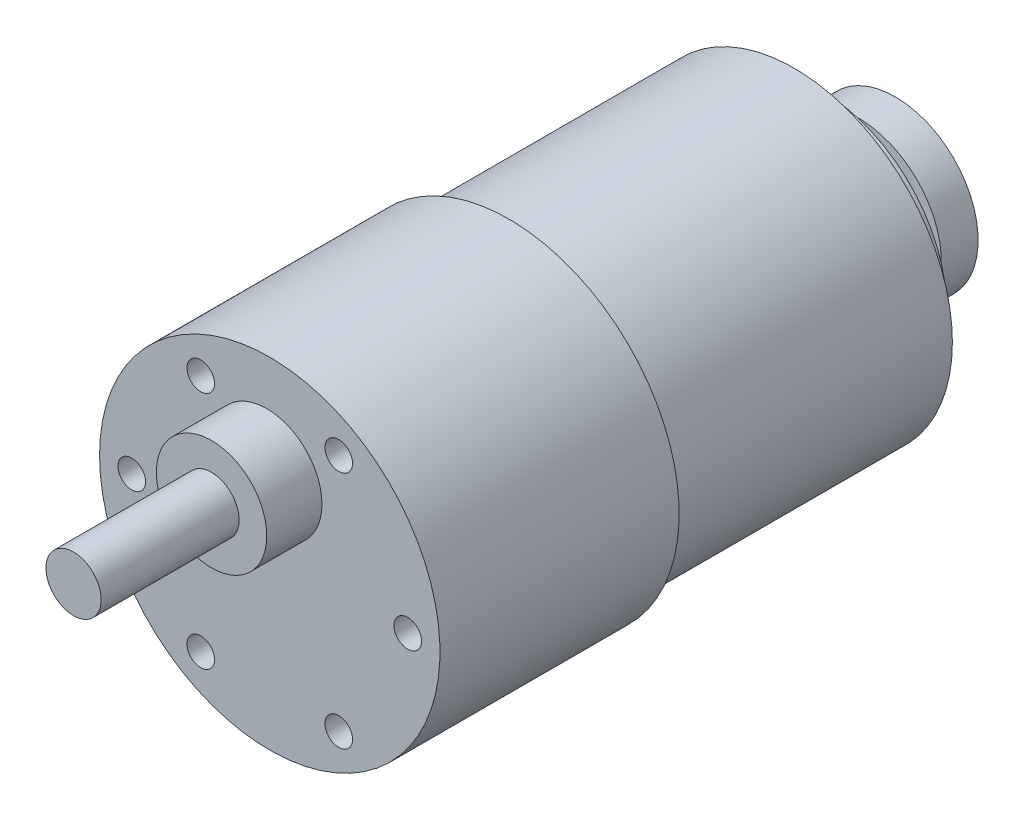
SolidWorks part; units mm, degrees
ref_plane "Plan de face" through (0, 0, 0) normal (0, 0, 1) x (1, 0, 0)
ref_plane "Plan de dessus" through (0, 0, 0) normal (0, 1, 0) x (1, 0, 0)
ref_plane "Plan de droite" through (0, 0, 0) normal (1, 0, 0) x (0, 0, -1)
sketch "Esquisse1" plane through (0, 0, 0) normal (0, 0, 1) x (1, 0, 0)
  circle A0 centre (0, 0) radius 18.5
  dimension "D1" = 37
extrude "Boss.-Extru.1" add sketch "Esquisse1" along normal blind 26
sketch "Esquisse2" plane through (0, 0, 0) normal (0, 0, -1) x (-1, 0, 0)
  circle A0 centre (0, 0) radius 17.2
  dimension "D1" = 34.4
extrude "Boss.-Extru.2" add sketch "Esquisse2" along normal blind 31
sketch "Esquisse3" plane through (0, 0, -31) normal (0, 0, -1) x (-1, 0, 0)
  circle A0 centre (0, 0) radius 13.55
  dimension "D1" = 27.1
extrude "Boss.-Extru.3" add sketch "Esquisse3" along normal blind 3
sketch "Esquisse4" plane through (0, 0, -34) normal (0, 0, -1) x (-1, 0, 0)
  circle A0 centre (0, 0) radius 0.75
  dimension "D1" = 1.5
extrude "Boss.-Extru.4" add sketch "Esquisse4" along normal blind 4
sketch "Esquisse5" plane through (0, 0, -38) normal (0, 0, -1) x (-1, 0, 0)
  circle A0 centre (0, 0) radius 9
  dimension "D1" = 18
extrude "Boss.-Extru.5" add sketch "Esquisse5" along normal blind 4
sketch "Esquisse6" plane through (0, 0, 26) normal (0, 0, 1) x (1, 0, 0)
  circle A0 centre (-0.327, 7.4929) radius 6
  circle A1 centre (0, 0) radius 18.5 construction
  dimension "D1" = 12
  dimension "D2" = 7.5
extrude "Boss.-Extru.7" add sketch "Esquisse6" along normal blind 6 contours A0
sketch "Esquisse8" plane through (0, 0, 32) normal (0, 0, 1) x (1, 0, 0)
  circle A0 centre (-0.327, 7.4929) radius 3
  dimension "D1" = 6
extrude "Boss.-Extru.8" add sketch "Esquisse8" along normal blind 15
sketch "Esquisse9" plane through (0, 0, 26) normal (0, 0, 1) x (1, 0, 0)
  circle A0 centre (15, 0) radius 1.5
  circle A1 centre (0, 0) radius 18.5 construction
  circle A2 centre (-0.327, 7.4929) radius 6 construction
  circle A3 centre (0, 0) radius 15
  circle A4 centre (7.5, -12.9904) radius 1.5
  circle A5 centre (-7.5, -12.9904) radius 1.5
  circle A6 centre (-15, 0) radius 1.5
  circle A7 centre (-7.5, 12.9904) radius 1.5
  circle A8 centre (7.5, 12.9904) radius 1.5
  dimension "D1" = 3
  dimension "D2" = 15
  dimension "D3" = 15.327
  dimension "D4" = 3
  dimension "D5" = 3
  dimension "D6" = 3
  dimension "D7" = 3
  dimension "D8" = 3
  dimension "D9" = 15
  dimension "D10" = 15
  dimension "D11" = 15
  dimension "D12" = 15
  dimension "D13" = 15
extrude "Enlèv. mat.-Extru.4" cut sketch "Esquisse9" against normal blind 5 contours A0 | A4 | A8 | A7 | A6 | A5
